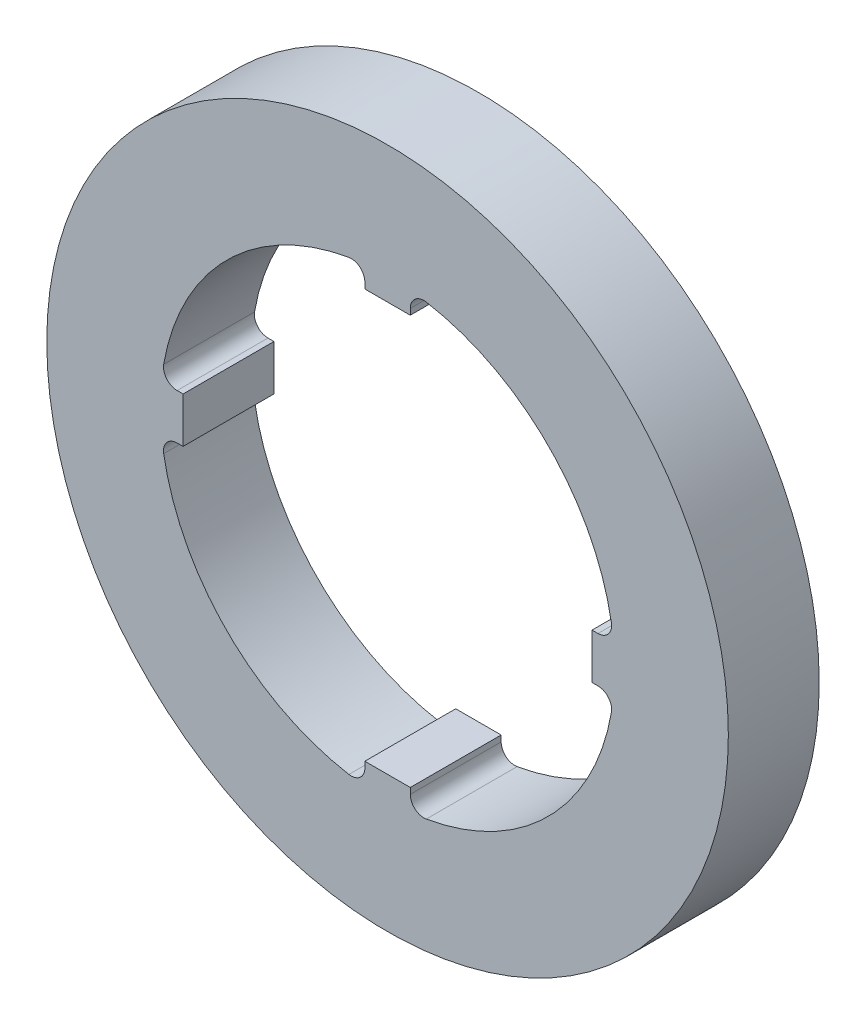
SolidWorks part; units mm, degrees
ref_plane "Front Plane" through (0, 0, 0) normal (0, 0, 1) x (1, 0, 0)
ref_plane "Top Plane" through (0, 0, 0) normal (0, 1, 0) x (1, 0, 0)
ref_plane "Right Plane" through (0, 0, 0) normal (1, 0, 0) x (0, 0, -1)
sketch "Sketch1" plane through (0, 0, 0) normal (0, 0, 1) x (1, 0, 0)
  line L0 (0, 0) -> (0, -67023.3573) construction
  line L1 (0, 0) -> (-67023.3573, 0) construction
  line L2 (-5, 46.3141) -> (-5, 45)
  line L3 (-5, 45) -> (5, 45)
  line L4 (5, 45) -> (5, 46.3141)
  line L5 (5, -45) -> (5, -46.3141)
  line L6 (-5, -45) -> (5, -45)
  line L7 (-5, -46.3141) -> (-5, -45)
  line L8 (46.3141, 5) -> (45, 5)
  line L9 (45, 5) -> (45, -5)
  line L10 (45, -5) -> (46.3141, -5)
  line L11 (-45, -5) -> (-46.3141, -5)
  line L12 (-45, 5) -> (-45, -5)
  line L13 (-46.3141, 5) -> (-45, 5)
  circle A0 centre (0, 0) radius 75
  arc A1 (-8.5106, 49.2704) -> (-49.2704, 8.5106) centre (0, 0) ccw
  arc A2 (5, 46.3141) -> (8.5106, 49.2704) centre (8, 46.3141) cw
  arc A3 (-5, 46.3141) -> (-8.5106, 49.2704) centre (-8, 46.3141) ccw
  arc A4 (-5, -46.3141) -> (-8.5106, -49.2704) centre (-8, -46.3141) cw
  arc A5 (5, -46.3141) -> (8.5106, -49.2704) centre (8, -46.3141) ccw
  arc A6 (8.5106, -49.2704) -> (49.2704, -8.5106) centre (0, 0) ccw
  arc A7 (49.2704, 8.5106) -> (8.5106, 49.2704) centre (0, 0) ccw
  arc A8 (46.3141, 5) -> (49.2704, 8.5106) centre (46.3141, 8) ccw
  arc A9 (46.3141, -5) -> (49.2704, -8.5106) centre (46.3141, -8) cw
  arc A10 (-46.3141, -5) -> (-49.2704, -8.5106) centre (-46.3141, -8) ccw
  arc A11 (-46.3141, 5) -> (-49.2704, 8.5106) centre (-46.3141, 8) cw
  arc A12 (-49.2704, -8.5106) -> (-8.5106, -49.2704) centre (0, 0) ccw
  point P29 (49.7494, 5)
  point P40 (-49.7494, 5)
  dimension "D1" = 150
  dimension "D2" = 100
  dimension "D4" = 3
  dimension "D8" = 3
  dimension "D3" = 10
  dimension "D5" = 45
  dimension "D6" = 10
  dimension "D7" = 45
extrude "Boss-Extrude1" add sketch "Sketch1" along normal mid plane 20
